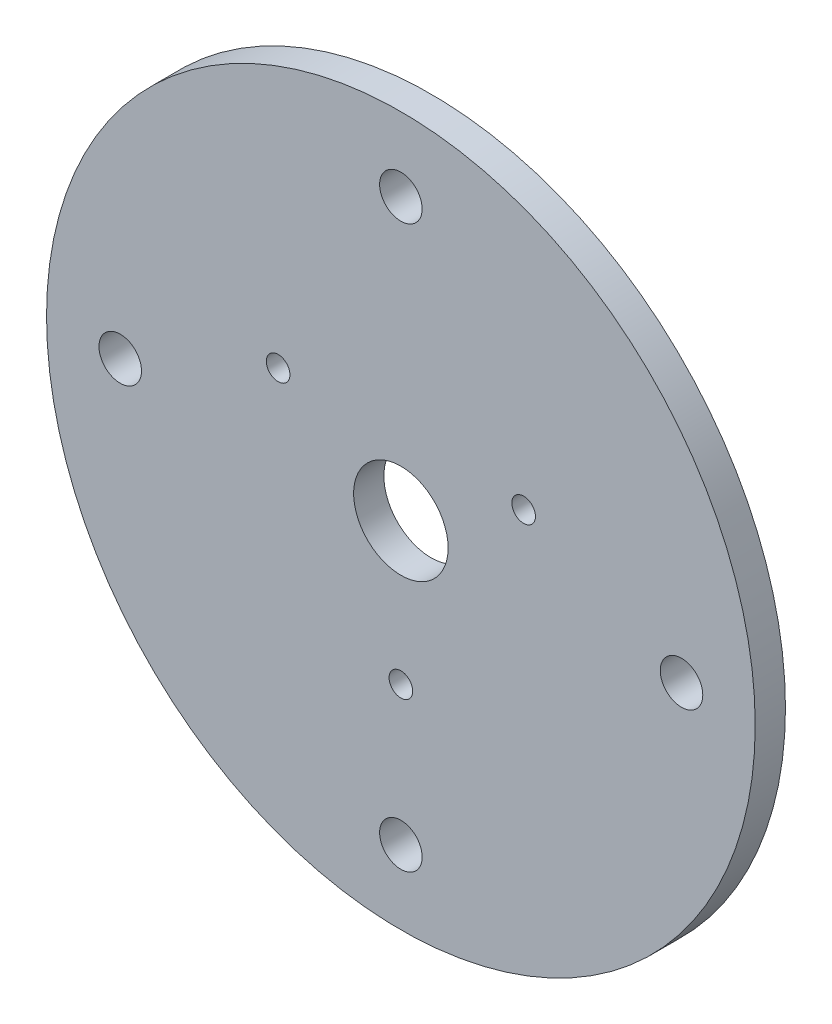
SolidWorks part; units mm, degrees
ref_plane "Front Plane" through (0, 0, 0) normal (0, 0, 1) x (1, 0, 0)
ref_plane "Top Plane" through (0, 0, 0) normal (0, 1, 0) x (1, 0, 0)
ref_plane "Right Plane" through (0, 0, 0) normal (1, 0, 0) x (0, 0, -1)
sketch "Sketch1" plane through (0, 0, 0) normal (0, 0, 1) x (1, 0, 0)
  line L0 (0, 0) -> (0, 37.5) construction
  line L1 (0, 0) -> (-12.9904, 7.5) construction
  circle A0 centre (0, 0) radius 37.5
  circle A1 centre (0, 29.7) radius 2.25
  circle A2 centre (0, 0) radius 5
  circle A3 centre (29.7, 0) radius 2.25
  circle A4 centre (0, -29.7) radius 2.25
  circle A5 centre (-29.7, 0) radius 2.25
  circle A6 centre (-12.9904, 7.5) radius 1.25
  circle A7 centre (12.9904, 7.5) radius 1.25
  circle A8 centre (0, -15) radius 1.25
  point P16 (0, 0)
  point P17 (16.5063, -4.9598)
  point P18 (0, 0)
  point P22 (0, 0)
  dimension "D1" = 75
  dimension "D3" = 4.5
  dimension "D4" = 10
  dimension "D8" = 2.5
  dimension "D2" = 29.7
  dimension "D6" = 15
  dimension "D7" = 60
  dimension "D5" = 4
  dimension "D9" = 3
extrude "Boss-Extrude1" add sketch "Sketch1" along normal blind 3.2
